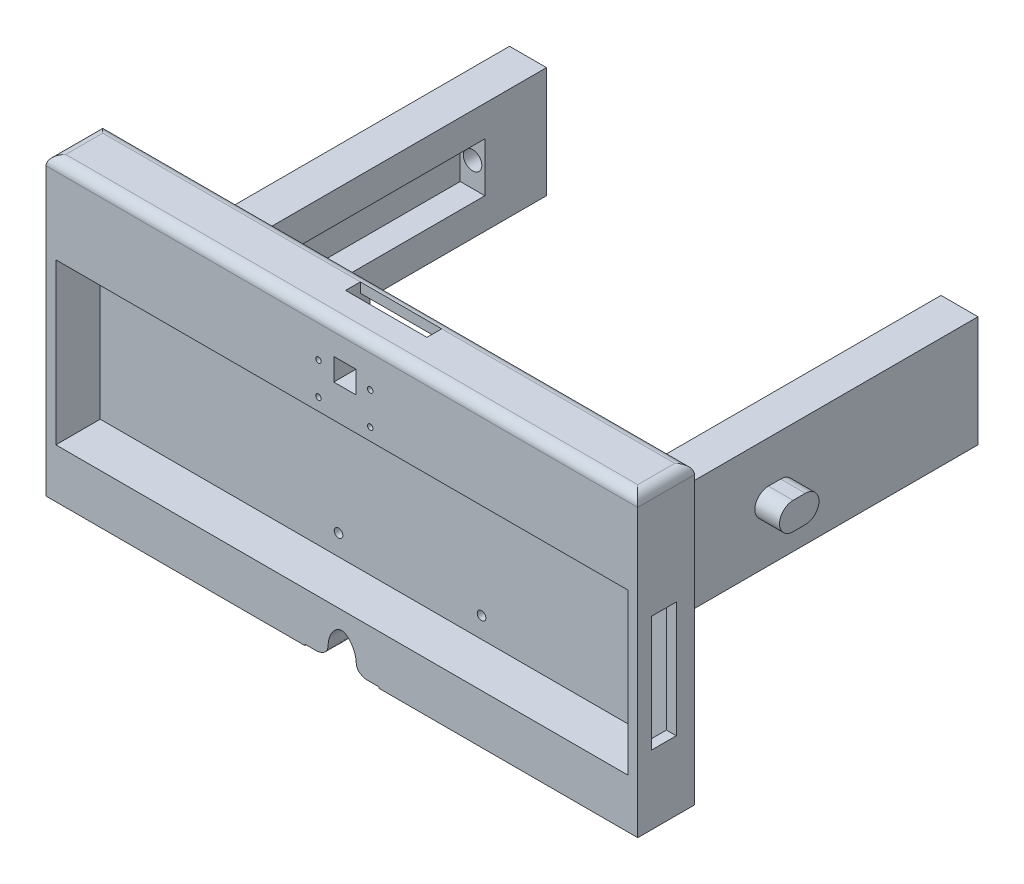
SolidWorks part; units mm, degrees
ref_plane "Plan de face" through (0, 0, 0) normal (0, 0, 1) x (1, 0, 0)
ref_plane "Plan de dessus" through (0, 0, 0) normal (0, 1, 0) x (1, 0, 0)
ref_plane "Plan de droite" through (0, 0, 0) normal (1, 0, 0) x (0, 0, -1)
sketch "Esquisse1" plane through (0, 0, 0) normal (0, 0, 1) x (1, 0, 0)
  line L1 (0, 0) -> (-240, 0)
  line L2 (0, 0) -> (0, -120)
  line L3 (0, -120) -> (-240, -120)
  line L4 (-240, 0) -> (-240, -120)
  dimension "D1" = 240
  dimension "D2" = 120
extrude "Boss.-Extru.1" add sketch "Esquisse1" along normal blind 23
sketch "Esquisse2" plane through (0, 0, 23) normal (0, 0, 1) x (1, 0, 0)
  line L0 (0, 0) -> (-240, 0) construction
  line L1 (-4, -35) -> (-236, -35)
  line L2 (-4, -35) -> (-4, -100)
  line L3 (-4, -100) -> (-236, -100)
  line L4 (-236, -35) -> (-236, -100)
  line L5 (-240, 0) -> (-240, -120) construction
  dimension "D1" = 232
  dimension "D2" = 35
  dimension "D3" = 4
  dimension "D4" = 65
extrude "Enlèv. mat.-Extru.1" cut sketch "Esquisse2" against normal blind 18
fillet "Congé1" radius 4 4 edges at (0, 0, 11.5) (-240, 0, 11.5) (-120, 0, 0) (-120, 0, 23)
sketch "Esquisse7" plane through (0, 0, 5) normal (0, 0, 1) x (1, 0, 0)
  line L0 (-4, -100) -> (-4, -35) construction
  line L2 (-4, -35) -> (-236, -35) construction
  circle A0 centre (-139.35, -42.66) radius 1.75
  circle A1 centre (-139.35, -91.66) radius 1.75
  circle A2 centre (-81.35, -91.66) radius 1.75
  circle A3 centre (-81.35, -42.66) radius 1.75
  dimension "D1" = 3.5
  dimension "D2" = 58
  dimension "D3" = 49
  dimension "D4" = 49
  dimension "D6" = 77.35
  dimension "D8" = 7.66
extrude "Enlèv. mat.-Extru.3" cut sketch "Esquisse7" against normal blind 10
sketch "Esquisse14" plane through (-4, 0, 0) normal (-1, 0, 0) x (0, 0, 1)
  line L0 (5, -35) -> (23, -35) construction
  line L1 (7.3634, -45) -> (17.3634, -45)
  line L2 (7.3634, -45) -> (7.3634, -92)
  line L3 (7.3634, -92) -> (17.3634, -92)
  line L4 (17.3634, -45) -> (17.3634, -92)
  line L5 (5, -100) -> (23, -100) construction
  dimension "D1" = 47
  dimension "D2" = 10
  dimension "D3" = 10
  dimension "D4" = 8
extrude "Enlèv. mat.-Extru.9" cut sketch "Esquisse14" against normal blind 43
sketch "Esquisse17" plane through (0, 0, 0) normal (0, 1, 0) x (1, 0, 0)
  line L0 (-4, -4) -> (-236, -4) construction
  line L1 (-98.5, -4) -> (-131.5, -4)
  line L2 (-98.5, -4) -> (-98.5, -10)
  line L3 (-98.5, -10) -> (-131.5, -10)
  line L4 (-131.5, -4) -> (-131.5, -10)
  line L5 (-236, -4) -> (-236, -19) construction
  line L6 (-4, -19) -> (-4, -4) construction
  point P8 (-98.5, -7)
  dimension "D1" = 33
  dimension "D2" = 6
  dimension "D3" = 104.5
  dimension "D4" = 94.5
extrude "Enlèv. mat.-Extru.11" cut sketch "Esquisse17" against normal blind 32
sketch "Esquisse18" plane through (0, 0, 0) normal (0, 0, -1) x (-1, 0, 0)
  line L0 (240, -4) -> (0, -4) construction
  line L1 (131.5, -4) -> (98.5, -4)
  line L2 (131.5, -4) -> (131.5, -32)
  line L3 (131.5, -32) -> (98.5, -32)
  line L4 (98.5, -4) -> (98.5, -32)
  line L6 (240, -4) -> (240, -120) construction
  dimension "D1" = 33
  dimension "D2" = 28
  dimension "D3" = 108.5
extrude "Enlèv. mat.-Extru.12" cut sketch "Esquisse18" against normal blind 7
sketch "Esquisse19" plane through (0, 0, 0) normal (0, 0, -1) x (-1, 0, 0)
  line L0 (0, -120) -> (0, -4) construction
  line L1 (25, -31) -> (40, -31)
  line L2 (25, -31) -> (25, -76)
  line L3 (25, -76) -> (40, -76)
  line L4 (40, -31) -> (40, -76)
  line L5 (200, -31) -> (215, -31)
  line L6 (200, -31) -> (200, -76)
  line L7 (200, -76) -> (215, -76)
  line L8 (215, -31) -> (215, -76)
  line L9 (98.5, -4) -> (0, -4) construction
  line L10 (240, -4) -> (131.5, -4) construction
  line L11 (240, -4) -> (240, -120) construction
  dimension "D1" = 15
  dimension "D2" = 15
  dimension "D3" = 160
  dimension "D4" = 25
  dimension "D5" = 27
  dimension "D6" = 45
  dimension "D7" = 45
  dimension "D8" = 27
  dimension "D9" = 25
extrude "Boss.-Extru.2" add sketch "Esquisse19" along normal blind 140
sketch "Esquisse20" plane through (-40, 0, 0) normal (-1, 0, 0) x (0, 0, 1)
  line L0 (-140, -76) -> (0, -76) construction
  line L1 (-15, -43.5) -> (-115, -43.5)
  line L2 (-15, -43.5) -> (-15, -63.5)
  line L3 (-15, -63.5) -> (-115, -63.5)
  line L4 (-115, -43.5) -> (-115, -63.5)
  line L5 (-140, -31) -> (0, -31) construction
  line L6 (0, -76) -> (0, -31) construction
  dimension "D1" = 100
  dimension "D2" = 20
  dimension "D3" = 12.5
  dimension "D4" = 12.5
  dimension "D5" = 15
extrude "Enlèv. mat.-Extru.13" cut sketch "Esquisse20" against normal blind 10
sketch "Esquisse21" plane through (0, 0, -115) normal (0, 0, 1) x (1, 0, 0)
  line L0 (-30, -63.5) -> (-40, -63.5) construction
  line L1 (-30, -43.5) -> (-30, -63.5) construction
  line L2 (-30, -43.5) -> (-40, -43.5) construction
  line L3 (-40, -43.5) -> (-40, -63.5) construction
  circle A0 centre (-35, -53.5) radius 3.75
  dimension "D1" = 7.5
  dimension "D2" = 10
  dimension "D3" = 5
  dimension "D4" = 10
  dimension "D5" = 5
extrude "Enlèv. mat.-Extru.14" cut sketch "Esquisse21" against normal blind 40
sketch "Esquisse22" plane through (-200, 0, 0) normal (1, 0, 0) x (0, 0, -1)
  line L0 (0, -31) -> (0, -76) construction
  line L1 (15, -43.5) -> (115, -43.5)
  line L2 (15, -43.5) -> (15, -63.5)
  line L3 (15, -63.5) -> (115, -63.5)
  line L4 (115, -43.5) -> (115, -63.5)
  line L5 (140, -31) -> (0, -31) construction
  dimension "D1" = 100
  dimension "D2" = 15
  dimension "D3" = 20
  dimension "D4" = 12.5
extrude "Enlèv. mat.-Extru.15" cut sketch "Esquisse22" against normal blind 10
sketch "Esquisse23" plane through (0, 0, -115) normal (0, 0, 1) x (1, 0, 0)
  line L0 (-200, -63.5) -> (-200, -43.5) construction
  line L1 (-210, -63.5) -> (-200, -63.5) construction
  circle A0 centre (-205, -53.5) radius 3.75
  dimension "D1" = 7.5
  dimension "D2" = 5
  dimension "D3" = 10
extrude "Enlèv. mat.-Extru.16" cut sketch "Esquisse23" against normal blind 40
sketch "Esquisse25" plane through (-25, 0, 0) normal (1, 0, 0) x (0, 0, -1)
  line L0 (55, -53.5) -> (60, -53.5) construction
  line L1 (55, -48) -> (60, -48)
  line L2 (55, -59) -> (60, -59)
  line L3 (140, -31) -> (140, -76) construction
  line L4 (140, -76) -> (0, -76) construction
  line L5 (140, -31) -> (0, -31) construction
  arc A0 (55, -48) -> (55, -59) centre (55, -53.5) ccw
  arc A1 (60, -59) -> (60, -48) centre (60, -53.5) ccw
  point P2 (57.5, -53.5)
  dimension "D2" = 5
  dimension "D1" = 11
  dimension "D3" = 80
  dimension "D4" = 22.5
  dimension "D5" = 22.5
extrude "Boss.-Extru.3" add sketch "Esquisse25" along normal blind 10
sketch "Esquisse26" plane through (-215, 0, 0) normal (-1, 0, 0) x (0, 0, 1)
  line L0 (-60, -53.5) -> (-55, -53.5) construction
  line L1 (-60, -48) -> (-55, -48)
  line L2 (-60, -59) -> (-55, -59)
  line L3 (-140, -76) -> (-140, -31) construction
  line L4 (-140, -76) -> (0, -76) construction
  line L5 (-140, -31) -> (0, -31) construction
  arc A0 (-60, -48) -> (-60, -59) centre (-60, -53.5) ccw
  arc A1 (-55, -59) -> (-55, -48) centre (-55, -53.5) ccw
  point P2 (-57.5, -53.5)
  dimension "D1" = 11
  dimension "D2" = 5
  dimension "D3" = 80
  dimension "D4" = 22.5
  dimension "D5" = 22.5
extrude "Boss.-Extru.4" add sketch "Esquisse26" along normal blind 10
sketch "Esquisse30" plane through (0, 0, 10) normal (0, 0, -1) x (-1, 0, 0)
  line L0 (131.5, -32) -> (131.5, -4) construction
  line L1 (98.5, -32) -> (131.5, -32) construction
  line L3 (114.29, -12.58) -> (123.29, -12.58)
  line L4 (114.29, -12.58) -> (114.29, -21.58)
  line L5 (114.29, -21.58) -> (123.29, -21.58)
  line L6 (123.29, -12.58) -> (123.29, -21.58)
  circle A0 centre (108.5, -30) radius 1.1
  circle A1 centre (129.5, -30) radius 1.1
  circle A2 centre (129.5, -16.96) radius 1.1
  circle A3 centre (108.5, -16.96) radius 1.1
  dimension "D1" = 2.2
  dimension "D2" = 2
  dimension "D3" = 2
  dimension "D4" = 13.04
  dimension "D5" = 21
  dimension "D6" = 9
  dimension "D7" = 9
  dimension "D8" = 6.21
  dimension "D9" = 5.79
  dimension "D10" = 8.42
extrude "Enlèv. mat.-Extru.22" cut sketch "Esquisse30" against normal blind 30
sketch "Esquisse31" plane through (0, 0, 5) normal (0, 0, 1) x (1, 0, 0)
  line L0 (-4, -35) -> (-236, -35) construction
  line L1 (-88.35, -41) -> (-94.35, -41)
  line L2 (-88.35, -41) -> (-88.35, -44)
  line L3 (-88.35, -44) -> (-94.35, -44)
  line L4 (-94.35, -41) -> (-94.35, -44)
  circle A0 centre (-81.35, -42.66) radius 1.75 construction
  dimension "D1" = 6
  dimension "D2" = 3
  dimension "D3" = 7
  dimension "D4" = 6
extrude "Enlèv. mat.-Extru.23" cut sketch "Esquisse31" against normal blind 10
sketch "Esquisse32" plane through (0, 0, 23) normal (0, 0, 1) x (1, 0, 0)
  line L0 (-135, -119.5) -> (-135, -120)
  line L1 (-240, -120) -> (0, -120) construction
  line L2 (-135, -120) -> (-105, -120)
  line L3 (-105, -120) -> (-105, -119.5)
  line L4 (-105, -119.5) -> (-110, -119.5)
  line L5 (-135, -119.5) -> (-130, -119.5)
  line L9 (0, -120) -> (0, -4) construction
  line L10 (-240, -4) -> (-240, -120) construction
  spline S0 degree 3 poles (-130, -119.5) (-129.4115, -119.5) (-125.206, -118.2698) (-126.0705, -112.0493) (-119.87, -103.8687) (-113.8387, -112.3867) (-114.3989, -118.0756) (-110.9221, -119.5) (-110, -119.5) knots 0 0 0 0 0.144123 0.276785 0.509497 0.778688 0.880906 1 1 1 1
  dimension "D1" = 30
  dimension "D2" = 5
  dimension "D3" = 5
  dimension "D4" = 105
  dimension "D5" = 105
  dimension "D7" = 0.5
  dimension "D8" = 0.5
extrude "Enlèv. mat.-Extru.24" cut sketch "Esquisse32" against normal blind 40
